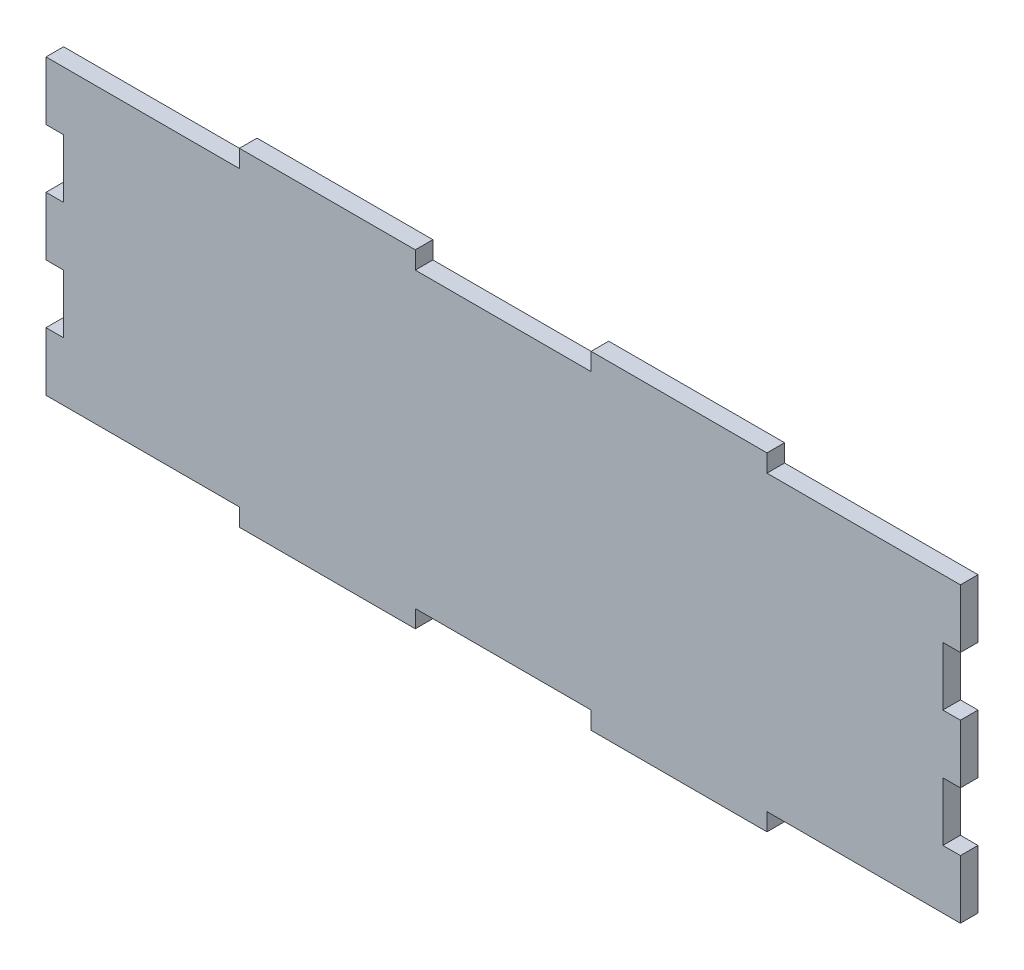
SolidWorks part; units mm, degrees
material "Pinho"
ref_plane "Plano frontal" through (0, 0, 0) normal (0, 0, 1) x (1, 0, 0)
ref_plane "Plano superior" through (0, 0, 0) normal (0, 1, 0) x (1, 0, 0)
ref_plane "Plano direito" through (0, 0, 0) normal (1, 0, 0) x (0, 0, -1)
sketch "Esboço1" plane through (0, 0, 0) normal (0, 0, 1) x (1, 0, 0)
  line L0 (45, 25) -> (75, 25)
  line L1 (-75, -25) -> (-45, -25)
  line L3 (-75, 25) -> (-45, 25)
  line L5 (-75, -25) -> (75, 25) construction
  line L6 (-75, 25) -> (75, -25) construction
  line L8 (-45, 25) -> (-45, 28)
  line L9 (-45, 28) -> (-15, 28)
  line L10 (-15, 25) -> (-15, 28)
  line L11 (-15, -25) -> (15, -25)
  line L12 (45, -25) -> (75, -25)
  line L14 (15, 25) -> (15, 28)
  line L15 (15, 28) -> (45, 28)
  line L16 (45, 25) -> (45, 28)
  line L17 (-15, 25) -> (15, 25)
  line L20 (-45, -25) -> (-45, -28)
  line L21 (-45, -28) -> (-15, -28)
  line L22 (-15, -25) -> (-15, -28)
  line L26 (15, -25) -> (15, -28)
  line L27 (15, -28) -> (45, -28)
  line L28 (45, -25) -> (45, -28)
  line L49 (75, 25) -> (78, 25)
  line L50 (78, 25) -> (78, 15)
  line L51 (78, 15) -> (75, 15)
  line L52 (75, 15) -> (75, 5)
  line L53 (75, 5) -> (78, 5)
  line L54 (78, 5) -> (78, -5)
  line L55 (78, -5) -> (75, -5)
  line L56 (75, -5) -> (75, -15)
  line L57 (75, -15) -> (78, -15)
  line L58 (78, -15) -> (78, -25)
  line L59 (78, -25) -> (75, -25)
  line L60 (-75, 25) -> (-78, 25)
  line L61 (-78, 25) -> (-78, 15)
  line L62 (-78, 15) -> (-75, 15)
  line L63 (-75, 15) -> (-75, 5)
  line L64 (-75, 5) -> (-78, 5)
  line L65 (-78, 5) -> (-78, -5)
  line L66 (-78, -5) -> (-75, -5)
  line L67 (-75, -5) -> (-75, -15)
  line L68 (-75, -15) -> (-78, -15)
  line L69 (-78, -15) -> (-78, -25)
  line L70 (-78, -25) -> (-75, -25)
  point P0 (0, 0)
  dimension "D1" = 150
  dimension "D2" = 50
  dimension "D3" = 30
  dimension "D4" = 30
  dimension "D5" = 30
  dimension "D6" = 30
  dimension "D7" = 3
  dimension "D8" = 3
  dimension "D9" = 3
  dimension "D10" = 3
  dimension "D11" = 30
  dimension "D12" = 30
  dimension "D13" = 30
  dimension "D14" = 30
  dimension "D15" = 10
  dimension "D16" = 3
  dimension "D17" = 3
extrude "Ressalto-extrusão1" add sketch "Esboço1" along normal blind 3
